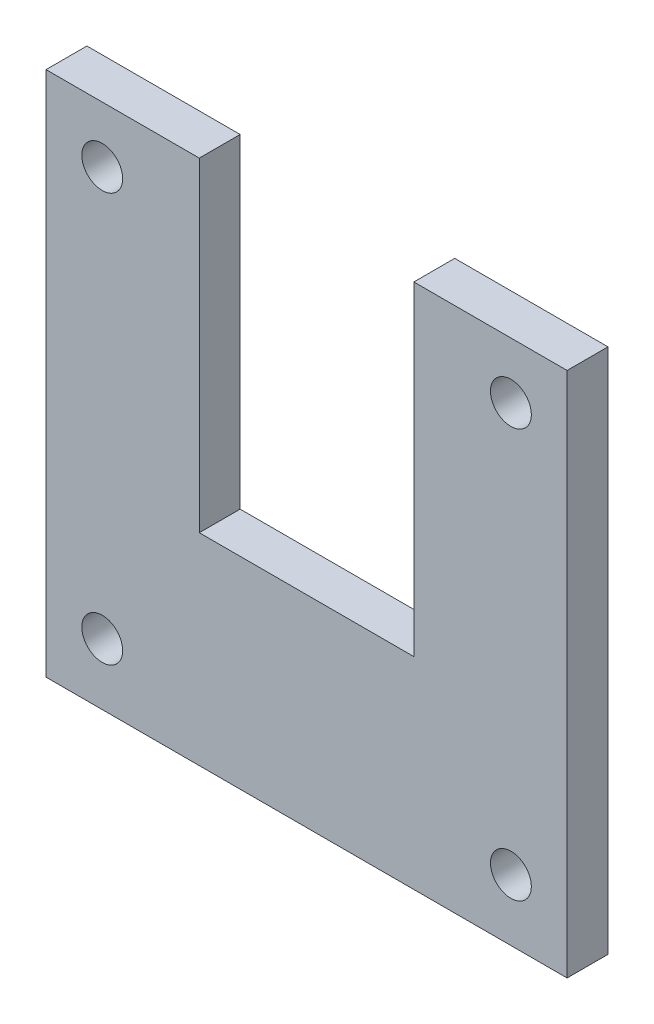
SolidWorks part; units mm, degrees
ref_plane "前视基准面" through (0, 0, 0) normal (0, 0, 1) x (1, 0, 0)
ref_plane "上视基准面" through (0, 0, 0) normal (0, 1, 0) x (1, 0, 0)
ref_plane "右视基准面" through (0, 0, 0) normal (1, 0, 0) x (0, 0, -1)
sketch "草图1" plane through (0, 0, 0) normal (0, 0, 1) x (1, 0, 0)
  line L0 (-24.2234, 19.5549) -> (-24.2234, -31.4451)
  line L1 (-18.7234, 14.0549) -> (21.2766, 14.0549) construction
  line L2 (-18.7234, 14.0549) -> (-18.7234, -25.9451) construction
  line L3 (-18.7234, -25.9451) -> (21.2766, -25.9451) construction
  line L4 (21.2766, 14.0549) -> (21.2766, -25.9451) construction
  line L6 (26.7766, 19.5549) -> (26.7766, -31.4451)
  line L7 (-24.2234, 19.5549) -> (26.7766, 19.5549)
  line L8 (-24.2234, -31.4451) -> (26.7766, -31.4451) construction
  line L9 (-24.2234, -31.4451) -> (-24.2234, -31.9451)
  line L10 (-24.2234, -31.9451) -> (26.7766, -31.9451)
  line L11 (26.7766, -31.9451) -> (26.7766, -31.4451)
  circle A0 centre (-18.7234, -25.9451) radius 2
  circle A1 centre (21.2766, -25.9451) radius 2
  circle A2 centre (-18.7234, 14.0549) radius 2
  circle A3 centre (21.2766, 14.0549) radius 2
  dimension "D1" = 40
  dimension "D2" = 40
extrude "凸台-拉伸1" add sketch "草图1" along normal blind 4
sketch "草图2" plane through (0, 0, 4) normal (0, 0, 1) x (1, 0, 0)
  line L0 (26.7766, 19.5549) -> (-24.2234, 19.5549) construction
  line L1 (-9.2234, 19.5549) -> (11.7766, 19.5549)
  line L2 (-9.2234, 19.5549) -> (-9.2234, -12.2021)
  line L3 (-9.2234, -12.2021) -> (11.7766, -12.2021)
  line L4 (11.7766, 19.5549) -> (11.7766, -12.2021)
  line L5 (-24.2234, 19.5549) -> (-24.2234, -31.9451) construction
  line L6 (26.7766, -31.9451) -> (26.7766, 19.5549) construction
  line L7 (-24.2234, -27.2021) -> (26.7766, -27.2021) construction
  dimension "D1" = 15
  dimension "D2" = 15
  dimension "D3" = 15
extrude "切除-拉伸1" cut sketch "草图2" against normal blind 4
